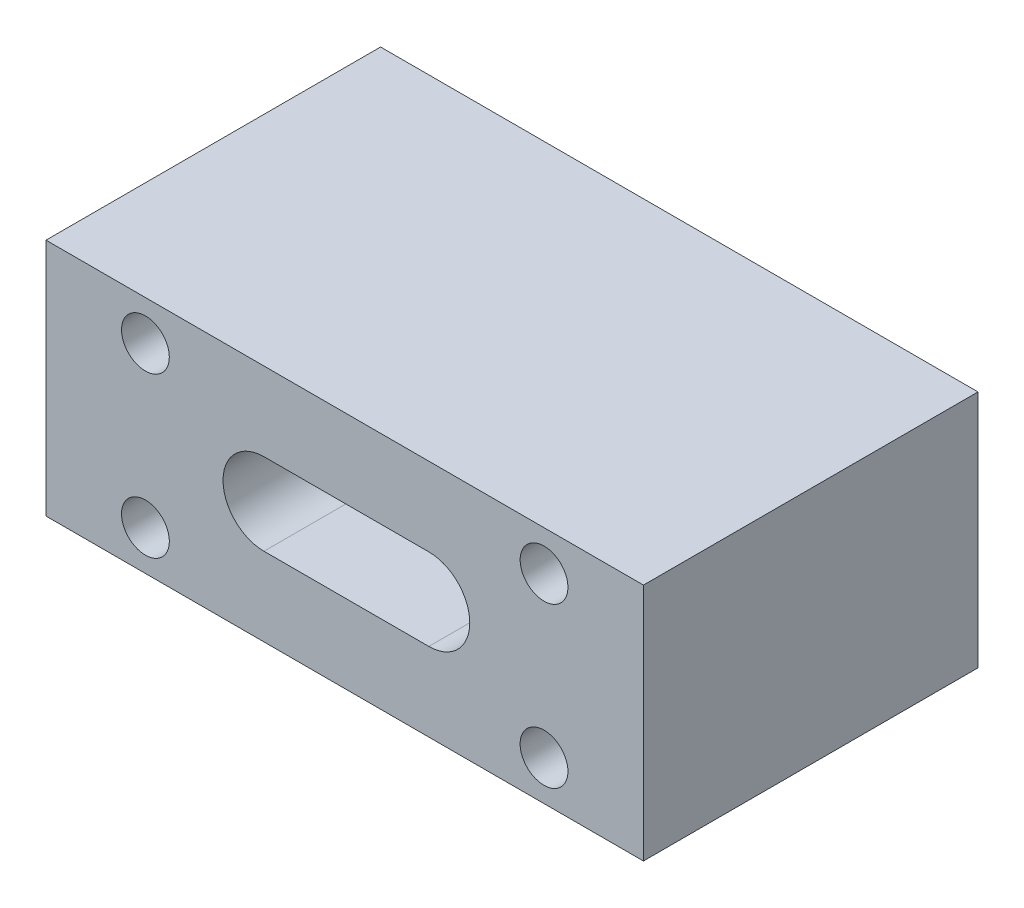
SolidWorks part; units mm, degrees
ref_plane "Plan de face" through (0, 0, 0) normal (0, 0, 1) x (1, 0, 0)
ref_plane "Plan de dessus" through (0, 0, 0) normal (0, 1, 0) x (1, 0, 0)
ref_plane "Plan de droite" through (0, 0, 0) normal (1, 0, 0) x (0, 0, -1)
sketch "Esquisse1" plane through (0, 0, 0) normal (0, 0, 1) x (1, 0, 0)
  line L0 (0, 0) -> (0, -132.7564) construction
  line L1 (-125, -50) -> (125, -50)
  line L2 (-125, -50) -> (-125, 50)
  line L3 (-125, 50) -> (125, 50)
  line L4 (125, -50) -> (125, 50)
  line L5 (-125, -50) -> (125, 50) construction
  line L6 (-125, 50) -> (125, -50) construction
  line L7 (0, 0) -> (170.9824, 0) construction
  line L8 (-33.7872, 0) -> (35.1969, 0) construction
  line L9 (-33.7872, 17.1322) -> (35.1969, 17.1322)
  line L10 (-33.7872, -17.1322) -> (35.1969, -17.1322)
  circle A0 centre (-83.4028, 33.3611) radius 10
  arc A1 (-33.7872, 17.1322) -> (-33.7872, -17.1322) centre (-33.7872, 0) ccw
  arc A2 (35.1969, -17.1322) -> (35.1969, 17.1322) centre (35.1969, 0) ccw
  circle A3 centre (83.4028, 33.3611) radius 10
  circle A4 centre (83.4028, -33.3611) radius 10
  circle A5 centre (-83.4028, -33.3611) radius 10
  point P0 (0, 0)
  point P14 (0.7048, 0)
  dimension "D3" = 20
  dimension "D1" = 250
  dimension "D2" = 100
extrude "Boss.-Extru.1" add sketch "Esquisse1" along normal blind 140
